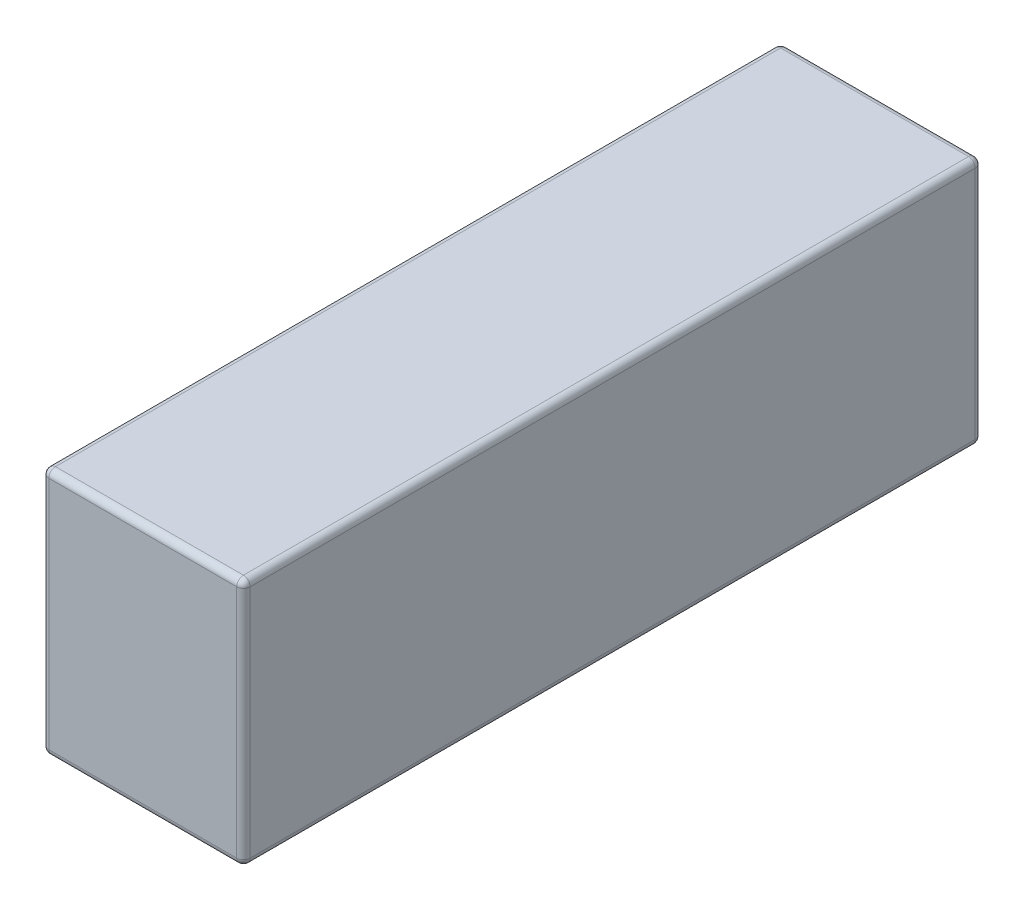
SolidWorks part; units mm, degrees
ref_plane "Front Plane" through (0, 0, 0) normal (0, 0, 1) x (1, 0, 0)
ref_plane "Top Plane" through (0, 0, 0) normal (0, 1, 0) x (1, 0, 0)
ref_plane "Right Plane" through (0, 0, 0) normal (1, 0, 0) x (0, 0, -1)
sketch "Sketch1" plane through (0, 0, 0) normal (0, 1, 0) x (1, 0, 0)
  line L1 (15, -59.5536) -> (-15, -59.5536)
  line L2 (15, -59.5536) -> (15, 50.4464)
  line L3 (15, 50.4464) -> (-15, 50.4464)
  line L4 (-15, -59.5536) -> (-15, 50.4464)
  line L5 (15, -59.5536) -> (-15, 50.4464) construction
  line L6 (15, 50.4464) -> (-15, -59.5536) construction
  point P0 (0, -4.5536)
  dimension "D1" = 30
  dimension "D2" = 110
extrude "Boss-Extrude1" add sketch "Sketch1" along normal blind 37
fillet "Fillet1" radius 1 12 edges at (0, 0, -50.4464) (-15, 18.5, -50.4464) (-15, 0, 4.5536) (-15, 18.5, 59.5536) (0, 0, 59.5536) (0, 37, -50.4464) (0, 37, 59.5536) (-15, 37, 4.5536) (15, 18.5, 59.5536) (15, 37, 4.5536) (15, 18.5, -50.4464) (15, 0, 4.5536)
